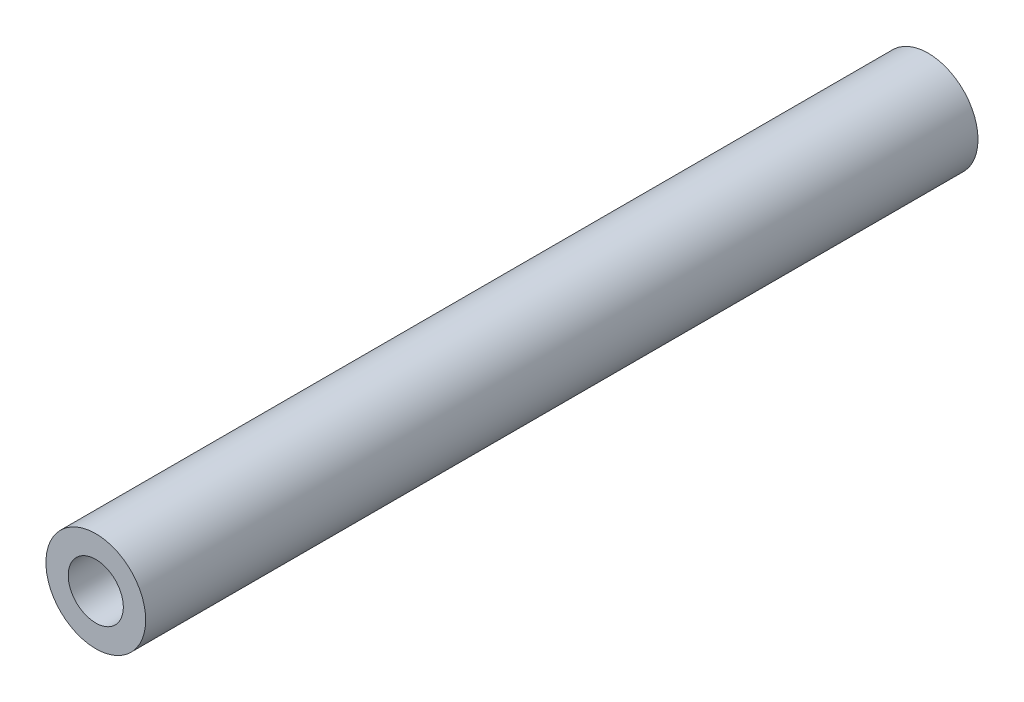
SolidWorks part; units mm, degrees
ref_plane "Piano frontale" through (0, 0, 0) normal (0, 0, 1) x (1, 0, 0)
ref_plane "Piano superiore" through (0, 0, 0) normal (0, 1, 0) x (1, 0, 0)
ref_plane "Piano destro" through (0, 0, 0) normal (1, 0, 0) x (0, 0, -1)
sketch "Schizzo1" plane through (0, 0, 0) normal (0, 0, 1) x (1, 0, 0)
  circle A0 centre (0, 0) radius 2.985
  dimension "D1" = 5.97
extrude "Estrusione-Estrusione1" add sketch "Schizzo1" along normal mid plane 49.82
sketch "Schizzo2" plane through (0, 0, 24.91) normal (0, 0, 1) x (1, 0, 0)
  circle A0 centre (0, 0) radius 1.6
  dimension "D1" = 3.2
extrude "Taglio-Estrusione1" cut sketch "Schizzo2" against normal through all
hole_wizard "Foro filettato M4x0.7-1" positions "Schizzo4" profile "Schizzo3" tap size "M4x0.7" standard "Ansi Metric"
sketch "Schizzo4" plane through (0, 0, 24.91) normal (0, 0, 1) x (1, 0, 0)
  point P0 (0, 0)
sketch "Schizzo3" plane through (0, 0, 24.91) normal (1, 0, 0) x (0, -1, 0)
  line L0 (0, 0) -> (0, 12.9914)
  line L1 (0, 12.9914) -> (1.65, 12)
  line L2 (1.65, 12) -> (1.65, 0)
  line L5 (1.65, 0) -> (0, 0)
  line L10 (0, 12.9914) -> (-1.65, 12) construction
  line L11 (0, -6.35) -> (0, 107.95) construction
  dimension "Tap Drill Dia." = 3.3
  dimension "Tap Drill Depth" = 12
  dimension "Drill Angle" = 118
cosmetic thread "Filettatura del foro1" parameters "D1"=0, "D2"=4.3
mirror "Specchia1" about plane through (0, 0, 0) normal (0, 0, 1) of "Foro filettato M4x0.7-1"
